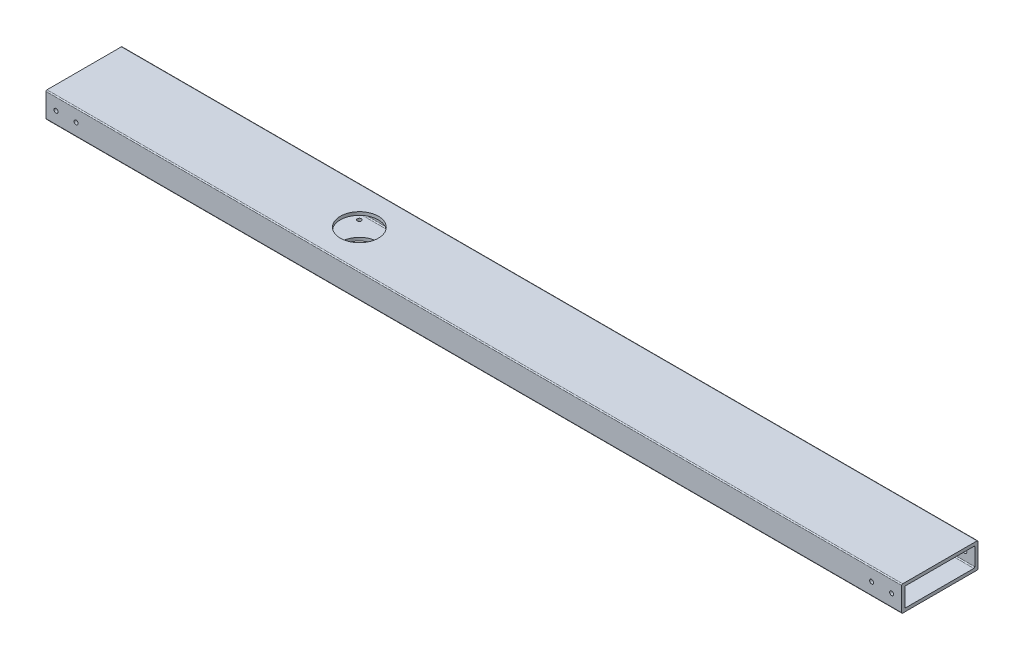
SolidWorks part; units mm, degrees
ref_plane "Front Plane" through (0, 0, 0) normal (0, 0, 1) x (1, 0, 0)
ref_plane "Top Plane" through (0, 0, 0) normal (0, 1, 0) x (1, 0, 0)
ref_plane "Right Plane" through (0, 0, 0) normal (1, 0, 0) x (0, 0, -1)
sketch "Sketch1" plane through (0, 0, 0) normal (1, 0, 0) x (0, 0, -1)
  line L1 (38.1, -12.7) -> (-38.1, -12.7)
  line L2 (38.1, -12.7) -> (38.1, 12.7)
  line L3 (38.1, 12.7) -> (-38.1, 12.7)
  line L4 (-38.1, -12.7) -> (-38.1, 12.7)
  line L5 (38.1, -12.7) -> (-38.1, 12.7) construction
  line L6 (38.1, 12.7) -> (-38.1, -12.7) construction
  line L7 (34.925, -9.525) -> (-34.925, -9.525)
  line L8 (34.925, -9.525) -> (34.925, 9.525)
  line L9 (34.925, 9.525) -> (-34.925, 9.525)
  line L10 (-34.925, -9.525) -> (-34.925, 9.525)
  line L11 (34.925, -9.525) -> (-34.925, 9.525) construction
  line L12 (34.925, 9.525) -> (-34.925, -9.525) construction
  point P0 (0, 0)
  point P6 (0, 0)
  dimension "D1" = 76.2
  dimension "D2" = 25.4
  dimension "D3" = 3.175
  dimension "D4" = 3.175
extrude "Boss-Extrude1" add sketch "Sketch1" along normal mid plane 854.4
fillet "Fillet1" radius 1 8 edges at (0, -12.7, -38.1) (0, 9.525, -34.925) (0, -9.525, 34.925) (0, 9.525, 34.925) (0, -12.7, 38.1) (0, -9.525, -34.925) (0, 12.7, -38.1) (0, 12.7, 38.1)
sketch "Sketch2" plane through (0, 12.7, 0) normal (0, 1, 0) x (1, 0, 0)
  line L0 (-427.2, 37.1) -> (-427.2, -37.1) construction
  circle A0 centre (-152.4, 0) radius 19
  dimension "D1" = 38
  dimension "D2" = 274.8
extrude "Cut-Extrude1" cut sketch "Sketch2" against normal through all
sketch "Sketch3" plane through (0, 12.7, 0) normal (0, 1, 0) x (1, 0, 0)
  line L1 (-197.2494, -25.5518) -> (-243.937, -25.5518)
  line L2 (-197.2494, -25.5518) -> (-197.2494, 25.5518)
  line L3 (-197.2494, 25.5518) -> (-243.937, 25.5518)
  line L4 (-243.937, -25.5518) -> (-243.937, 25.5518)
  line L5 (-197.2494, -25.5518) -> (-243.937, 25.5518) construction
  line L6 (-197.2494, 25.5518) -> (-243.937, -25.5518) construction
  point P0 (-220.5932, 0)
split line "Split Line1" [suppressed]
sketch "Sketch4" plane through (0, 0, 38.1) normal (0, 0, 1) x (1, 0, 0)
  line L0 (-427.2, 11.7) -> (-427.2, -11.7) construction
  point P0 (-417.2, 0)
  point P2 (-397.2, 0)
  dimension "D1" = 20
  dimension "D2" = 10
hole_wizard "Ø4.0mm Dowel Hole1" positions "Sketch4" profile "Sketch5" hole size "Ø4.0" standard "ANSI Metric" end condition through all
sketch "Sketch5" plane through (-417.2, 0, 38.1) normal (1, 0, 0) x (0, -1, 0)
  line L0 (0, 0) -> (0, 76.2)
  line L1 (0, 76.2) -> (2, 76.2)
  line L2 (2, 76.2) -> (2, 0)
  line L5 (2, 0) -> (0, 0)
  line L11 (0, -6.35) -> (0, 107.95) construction
  dimension "Thru Hole Dia." = 4
  dimension "Thru Hole Depth" = 76.2
mirror "Mirror1" about plane through (0, 0, 0) normal (1, 0, 0) of "Ø4.0mm Dowel Hole1"
hole_wizard "Ø4.0mm Dowel Hole2" positions "Sketch6" profile "Sketch7" hole size "Ø4.0" standard "ANSI Metric"
sketch "Sketch6" plane through (0, -12.7, 0) normal (0, -1, 0) x (-1, 0, 0)
  line L0 (123.8329, -28.5671) -> (180.9671, -28.5671) construction
  line L1 (180.9671, -28.5671) -> (180.9671, 28.5671) construction
  line L2 (180.9671, 28.5671) -> (123.8329, 28.5671) construction
  line L3 (123.8329, 28.5671) -> (123.8329, -28.5671) construction
  circle A1 centre (152.4, 0) radius 25.4 construction
  circle A2 centre (152.4, 0) radius 40.4 construction
  point P1 (180.9671, -28.5671)
  point P3 (180.9671, 28.5671)
  point P5 (123.8329, 28.5671)
  point P7 (123.8329, -28.5671)
  point P21 (123.8329, 0)
  point P203 (152.4, 28.5671)
  dimension "D1" = 50.8
  dimension "D2" = 15
sketch "Sketch7" plane through (-180.9671, -12.7, 28.5671) normal (1, 0, 0) x (0, 0, -1)
  line L0 (0, 0) -> (0, 3.175)
  line L1 (0, 3.175) -> (2, 3.175)
  line L2 (2, 3.175) -> (2, 0)
  line L5 (2, 0) -> (0, 0)
  line L11 (0, -6.35) -> (0, 107.95) construction
  dimension "Thru Hole Dia." = 4
  dimension "Thru Hole Depth" = 3.175
